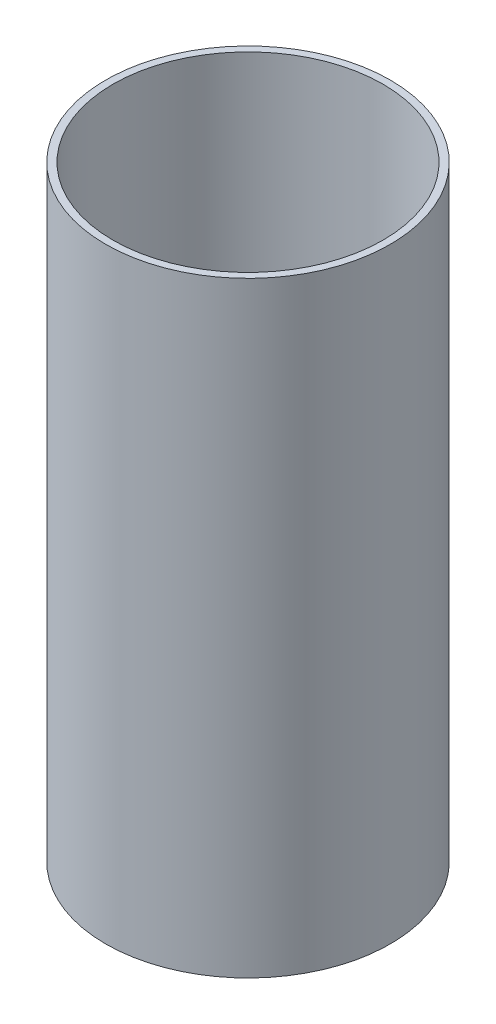
SolidWorks part; units mm, degrees
material "PVC Rigid"
ref_plane "Front Plane" through (0, 0, 0) normal (0, 0, 1) x (1, 0, 0)
ref_plane "Top Plane" through (0, 0, 0) normal (0, 1, 0) x (1, 0, 0)
ref_plane "Right Plane" through (0, 0, 0) normal (1, 0, 0) x (0, 0, -1)
sketch "Sketch1" plane through (0, 0, 0) normal (0, 1, 0) x (1, 0, 0)
  circle A0 centre (0, 0) radius 93.6625
  circle A1 centre (0, 0) radius 88.9
  dimension "D1" = 187.325
  dimension "D2" = 177.8
extrude "Boss-Extrude1" add sketch "Sketch1" along normal mid plane 398.78
ref_plane "Plane1" through (0, 0, 93.6625) normal (0, 0, 1) x (1, 0, 0)
sketch "Sketch3" plane through (0, 0, 93.6625) normal (0, 0, 1) x (1, 0, 0)
  line L0 (0, -103.0288) -> (0, 103.0288) construction
  line L1 (-93.6625, -199.39) -> (93.6625, -199.39) construction
  circle A0 centre (0, -193.04) radius 1.4351
  dimension "D1" = 2.8702
  dimension "D2" = 6.35
extrude "Cut-Extrude1" [suppressed] cut sketch "Sketch3" against normal blind 19.304
pattern_circular "CirPattern1" [suppressed] count 12 over 360
mirror "Mirror1" [suppressed] about plane through (0, 0, 0) normal (0, 1, 0)
sketch "Sketch4" [suppressed] plane through (0, 0, 93.6625) normal (0, 0, 1) x (1, 0, 0)
  line L0 (0, -103.0288) -> (0, 103.0288) construction
  circle A0 centre (0, 64.3636) radius 1.4351
  circle A1 centre (0, -64.3636) radius 1.4351
  circle A2 centre (0, 193.04) radius 1.4351 construction
  circle A3 centre (0, -193.04) radius 1.4351 construction
  dimension "D1" = 128.6764
  dimension "D2" = 128.6764
  dimension "D3" = 2.8702
  dimension "D4" = 2.8702
extrude "Cut-Extrude2" [suppressed] cut sketch "Sketch4" against normal blind 43.18
pattern_circular "CirPattern2" [suppressed] count 3 over 360
